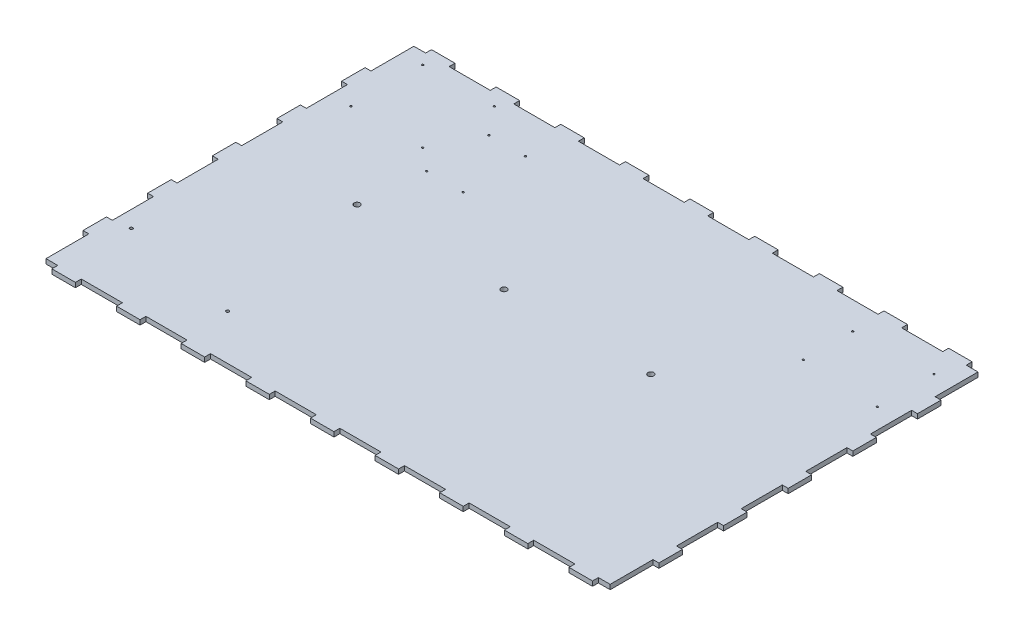
SolidWorks part; units mm, degrees
material "Acrylic (Medium-high impact)"
ref_plane "Front Plane" through (0, 0, 0) normal (0, 0, 1) x (1, 0, 0)
ref_plane "Top Plane" through (0, 0, 0) normal (0, 1, 0) x (1, 0, 0)
ref_plane "Right Plane" through (0, 0, 0) normal (1, 0, 0) x (0, 0, -1)
sketch "Sketch1" plane through (0, 0, 0) normal (0, 1, 0) x (1, 0, 0)
  line L1 (240, -156.5) -> (-240, -156.5)
  line L2 (240, -156.5) -> (240, 156.5)
  line L3 (240, 156.5) -> (-240, 156.5)
  line L4 (-240, -156.5) -> (-240, 156.5)
  line L5 (240, -156.5) -> (-240, 156.5) construction
  line L6 (240, 156.5) -> (-240, -156.5) construction
  point P0 (0, 0)
  dimension "D1" = 480
  dimension "D2" = 313
extrude "Base" add sketch "Sketch1" along normal blind 4
sketch "Sketch2" plane through (0, 4, 0) normal (0, 1, 0) x (1, 0, 0)
  line L0 (240, 156.5) -> (-240, 156.5) construction
  line L1 (-10, 156.5) -> (10, 156.5)
  line L2 (-10, 156.5) -> (-10, 161.5)
  line L3 (-10, 161.5) -> (10, 161.5)
  line L4 (10, 156.5) -> (10, 161.5)
  point P6 (0, 156.5)
  dimension "D1" = 20
  dimension "D2" = 5
extrude "Top Tabs Definition" add sketch "Sketch2" along direction (0, -1, 0) on the side against the normal up to surface (4 mm away)
pattern_linear "Top Tabs Pattern" count 5 spacing 55 along (-1, 0, 0) count 5 spacing 55 along (1, 0, 0) of "Top Tabs Definition"
mirror "Bottom Tabs" about plane through (0, 0, 0) normal (0, 0, 1) of "Top Tabs Definition", "Top Tabs Pattern"
hole_wizard "Electronics Mounting Holes (1.5)" positions "Sketch4" profile "Sketch5" hole size "Ø1.5" standard "ANSI Metric" end condition up to next
sketch "Sketch4" plane through (0, 4, 0) normal (0, 1, 0) x (1, 0, 0)
  circle A0 centre (156.815, 91.15) radius 1 construction
  circle A1 centre (156.815, 133.06) radius 1 construction
  circle A2 centre (222.855, 136.235) radius 1 construction
  circle A3 centre (222.855, 87.975) radius 1 construction
  point P6 (-142.5, 122.8809)
  point P8 (-111.5, 122.8809)
  point P10 (-111.5, 69.8809)
  point P12 (-142.5, 69.8809)
  point P62 (-161.5, 85.4937)
  point P64 (-161.5, 146.4937)
  point P66 (-222.5, 146.4937)
  point P68 (-222.5, 85.4937)
  point P79 (156.815, 133.06)
  point P81 (222.855, 136.235)
  point P83 (222.855, 87.975)
  point P85 (156.815, 91.15)
sketch "Sketch5" plane through (-142.5, 4, -122.8809) normal (1, 0, 0) x (0, 0, 1)
  line L0 (0, 0) -> (0, 4)
  line L1 (0, 4) -> (0.75, 4)
  line L2 (0.75, 4) -> (0.75, 0)
  line L5 (0.75, 0) -> (0, 0)
  line L11 (0, -6.35) -> (0, 107.95) construction
  dimension "Thru Hole Dia." = 1.5
  dimension "Thru Hole Depth" = 4
sketch "Sketch7" plane through (0, 4, 0) normal (0, 1, 0) x (1, 0, 0)
  line L0 (-240, 156.5) -> (-240, -156.5) construction
  line L1 (-240, -10) -> (-245, -10)
  line L2 (-240, -10) -> (-240, 10)
  line L3 (-240, 10) -> (-245, 10)
  line L4 (-245, -10) -> (-245, 10)
  point P6 (-240, 0)
  dimension "D1" = 20
  dimension "D2" = 5
extrude "Left Tabs Definition" add sketch "Sketch7" against normal up to surface (4 mm away) up to face at (-142.5, 0, -122.1309)
pattern_linear "Left Tabs Pattern" count 3 spacing 55 along (0, 0, -1) count 3 spacing 55 along (0, 0, 1) of "Left Tabs Definition"
mirror "Right Tabs" about plane through (0, 0, 0) normal (1, 0, 0) of "Left Tabs Pattern", "Left Tabs Definition"
hole_wizard "M6 Clearance Hole1" positions "Sketch8" profile "Sketch9" hole size "M6x1.0" standard "ANSI Metric" end condition up to next
sketch "Sketch8" plane through (0, 4, 0) normal (0, 1, 0) x (1, 0, 0)
  circle A0 centre (-147.5, 15.6703) radius 5.5 construction
  circle A1 centre (-22.5, 15.6703) radius 5.5 construction
  circle A2 centre (102.5, 15.6703) radius 5.5 construction
  point P0 (-147.5, 15.6703)
  point P10 (-22.5, 15.6703)
  point P12 (102.5, 15.6703)
sketch "Sketch9" plane through (-147.5, 4, -15.6703) normal (1, 0, 0) x (0, 0, 1)
  line L0 (0, 0) -> (0, 4)
  line L1 (0, 4) -> (2.5, 4)
  line L2 (2.5, 4) -> (2.5, 0)
  line L5 (2.5, 0) -> (0, 0)
  line L11 (0, -6.35) -> (0, 107.95) construction
  dimension "Thru Hole Dia." = 5
  dimension "Thru Hole Depth" = 4
hole_wizard "Tap Drill for M3x0.5 Tap1" positions "Sketch10" profile "Sketch11" hole size "M3x0.5" standard "ANSI Metric" end condition up to next
sketch "Sketch10" plane through (0, 0, 0) normal (0, -1, 0) x (-1, 0, 0)
  circle A0 centre (226, -97.9463) radius 1.6 construction
  circle A1 centre (124, -117.9463) radius 1.6 construction
  point P0 (124, -117.9463)
  point P2 (226, -97.9463)
sketch "Sketch11" plane through (-124, 0, 117.9463) normal (1, 0, 0) x (0, 0, -1)
  line L0 (0, 0) -> (0, 4)
  line L1 (0, 4) -> (1.25, 4)
  line L2 (1.25, 4) -> (1.25, 0)
  line L5 (1.25, 0) -> (0, 0)
  line L11 (0, -6.35) -> (0, 107.95) construction
  dimension "Thru Hole Dia." = 2.5
  dimension "Thru Hole Depth" = 4
other "Freeze***"
